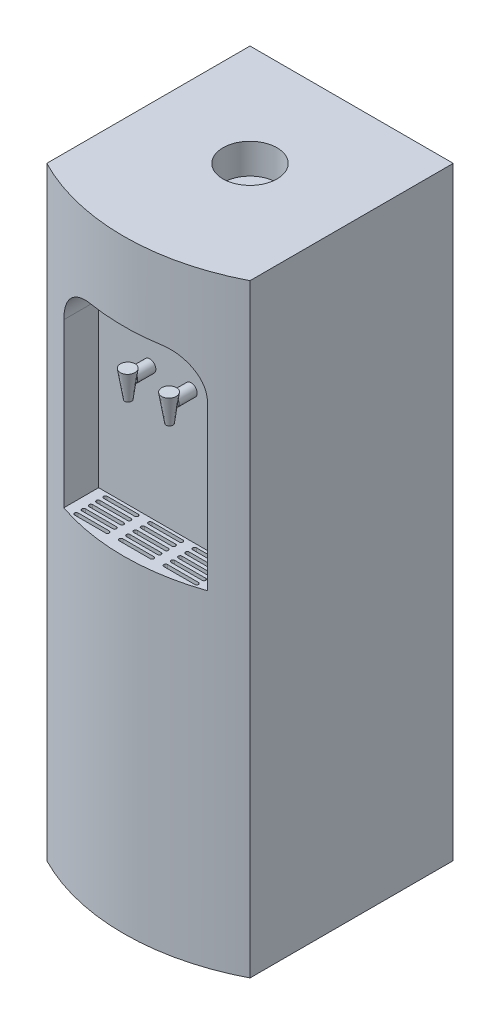
SolidWorks part; units mm, degrees
ref_plane "Front Plane" through (0, 0, 0) normal (0, 0, 1) x (1, 0, 0)
ref_plane "Top Plane" through (0, 0, 0) normal (0, 1, 0) x (1, 0, 0)
ref_plane "Right Plane" through (0, 0, 0) normal (1, 0, 0) x (0, 0, -1)
sketch "Sketch1" plane through (0, 0, 0) normal (0, 1, 0) x (1, 0, 0)
  line L1 (0, 0) -> (42.7396, 0)
  line L2 (0, 0) -> (0, -42.7396)
  line L4 (42.7396, 0) -> (42.7396, -42.7396)
  arc A0 (0, -42.7396) -> (42.7396, -42.7396) centre (21.3698, -1.442) ccw
extrude "Boss-Extrude1" add sketch "Sketch1" along normal blind 127
ref_plane "Plane1" through (0, 0, 127) normal (0, 0, 1) x (1, 0, 0)
sketch "Sketch2" plane through (0, 0, 127) normal (0, 0, 1) x (1, 0, 0)
  line L0 (6.2617, 110.6088) -> (0, 110.6088) construction
  line L1 (13.8817, 110.6088) -> (28.8579, 110.6088)
  line L2 (6.2617, 102.9888) -> (6.2617, 68.7343)
  line L3 (6.2617, 68.7343) -> (36.4779, 68.7343)
  line L4 (36.4779, 102.9888) -> (36.4779, 68.7343)
  line L5 (0, 127) -> (0, 0) construction
  line L6 (36.4779, 110.6088) -> (42.7396, 110.6088) construction
  line L7 (42.7396, 127) -> (42.7396, 0) construction
  arc A0 (28.8579, 110.6088) -> (36.4779, 102.9888) centre (28.8579, 102.9888) cw
  arc A1 (13.8817, 110.6088) -> (6.2617, 102.9888) centre (13.8817, 102.9888) ccw
  dimension "D1" = 7.62
extrude "Cut-Extrude1" cut sketch "Sketch2" against normal blind 88.9
sketch "Sketch4" plane through (0, 68.7343, 0) normal (0, 1, 0) x (1, 0, 0)
  line L0 (6.2617, -38.1) -> (36.4779, -38.1) construction
  line L1 (6.2617, -38.1) -> (36.4779, -38.1) construction
  line L2 (36.4779, -38.1) -> (36.4779, -45.4182) construction
  line L3 (6.2617, -38.1) -> (6.2617, -45.4182) construction
  line L4 (8.7222, -40.6541) -> (15.2596, -40.6541) construction
  line L5 (8.7222, -40.2731) -> (15.2596, -40.2731)
  line L6 (8.7222, -41.0351) -> (15.2596, -41.0351)
  line L7 (18.1011, -40.6541) -> (24.6385, -40.6541) construction
  line L8 (18.1011, -40.2731) -> (24.6385, -40.2731)
  line L9 (18.1011, -41.0351) -> (24.6385, -41.0351)
  line L10 (27.48, -40.6541) -> (34.0174, -40.6541) construction
  line L11 (27.48, -40.2731) -> (34.0174, -40.2731)
  line L12 (27.48, -41.0351) -> (34.0174, -41.0351)
  line L13 (8.3412, -40.6541) -> (6.2617, -40.6541) construction
  line L14 (34.3984, -40.6541) -> (36.4779, -40.6541) construction
  line L15 (15.6406, -40.6541) -> (17.7201, -40.6541) construction
  line L16 (25.0195, -40.6541) -> (27.099, -40.6541) construction
  line L17 (8.7222, -42.1781) -> (15.2596, -42.1781) construction
  line L18 (8.7222, -41.7971) -> (15.2596, -41.7971)
  line L19 (8.7222, -42.5591) -> (15.2596, -42.5591)
  line L20 (18.1011, -42.1781) -> (24.6385, -42.1781) construction
  line L21 (18.1011, -41.7971) -> (24.6385, -41.7971)
  line L22 (18.1011, -42.5591) -> (24.6385, -42.5591)
  line L23 (27.48, -42.1781) -> (34.0174, -42.1781) construction
  line L24 (27.48, -41.7971) -> (34.0174, -41.7971)
  line L25 (27.48, -42.5591) -> (34.0174, -42.5591)
  line L26 (8.7222, -43.7021) -> (15.2596, -43.7021) construction
  line L27 (8.7222, -43.3211) -> (15.2596, -43.3211)
  line L28 (8.7222, -44.0831) -> (15.2596, -44.0831)
  line L29 (18.1011, -43.7021) -> (24.6385, -43.7021) construction
  line L30 (18.1011, -43.3211) -> (24.6385, -43.3211)
  line L31 (18.1011, -44.0831) -> (24.6385, -44.0831)
  line L32 (27.48, -43.7021) -> (34.0174, -43.7021) construction
  line L33 (27.48, -43.3211) -> (34.0174, -43.3211)
  line L34 (27.48, -44.0831) -> (34.0174, -44.0831)
  line L35 (8.7222, -45.2261) -> (15.2596, -45.2261) construction
  line L36 (8.7222, -44.8451) -> (15.2596, -44.8451)
  line L37 (8.7222, -45.6071) -> (15.2596, -45.6071)
  line L38 (18.1011, -45.2261) -> (24.6385, -45.2261) construction
  line L39 (18.1011, -44.8451) -> (24.6385, -44.8451)
  line L40 (18.1011, -45.6071) -> (24.6385, -45.6071)
  line L41 (27.48, -45.2261) -> (34.0174, -45.2261) construction
  line L42 (27.48, -44.8451) -> (34.0174, -44.8451)
  line L43 (27.48, -45.6071) -> (34.0174, -45.6071)
  line L44 (8.7222, -40.6541) -> (15.2596, -40.6541) construction
  line L45 (8.7222, -40.2731) -> (15.2596, -40.2731)
  line L46 (8.7222, -41.0351) -> (15.2596, -41.0351)
  line L47 (18.1011, -40.6541) -> (24.6385, -40.6541) construction
  line L48 (18.1011, -40.2731) -> (24.6385, -40.2731)
  line L49 (18.1011, -41.0351) -> (24.6385, -41.0351)
  line L50 (27.48, -40.6541) -> (34.0174, -40.6541) construction
  line L51 (27.48, -40.2731) -> (34.0174, -40.2731)
  line L52 (27.48, -41.0351) -> (34.0174, -41.0351)
  line L53 (8.7222, -42.1781) -> (15.2596, -42.1781) construction
  line L54 (8.7222, -41.7971) -> (15.2596, -41.7971)
  line L55 (8.7222, -42.5591) -> (15.2596, -42.5591)
  line L56 (18.1011, -42.1781) -> (24.6385, -42.1781) construction
  line L57 (18.1011, -41.7971) -> (24.6385, -41.7971)
  line L58 (18.1011, -42.5591) -> (24.6385, -42.5591)
  line L59 (27.48, -42.1781) -> (34.0174, -42.1781) construction
  line L60 (27.48, -41.7971) -> (34.0174, -41.7971)
  line L61 (27.48, -42.5591) -> (34.0174, -42.5591)
  line L62 (8.7222, -43.7021) -> (15.2596, -43.7021) construction
  line L63 (8.7222, -43.3211) -> (15.2596, -43.3211)
  line L64 (8.7222, -44.0831) -> (15.2596, -44.0831)
  line L65 (18.1011, -43.7021) -> (24.6385, -43.7021) construction
  line L66 (18.1011, -43.3211) -> (24.6385, -43.3211)
  line L67 (18.1011, -44.0831) -> (24.6385, -44.0831)
  line L68 (27.48, -43.7021) -> (34.0174, -43.7021) construction
  line L69 (27.48, -43.3211) -> (34.0174, -43.3211)
  line L70 (27.48, -44.0831) -> (34.0174, -44.0831)
  line L71 (8.7222, -39.1301) -> (15.2596, -39.1301) construction
  line L72 (8.7222, -38.7491) -> (15.2596, -38.7491)
  line L73 (8.7222, -39.5111) -> (15.2596, -39.5111)
  line L74 (18.1011, -39.1301) -> (24.6385, -39.1301) construction
  line L75 (18.1011, -38.7491) -> (24.6385, -38.7491)
  line L76 (18.1011, -39.5111) -> (24.6385, -39.5111)
  line L77 (27.48, -39.1301) -> (34.0174, -39.1301) construction
  line L78 (27.48, -38.7491) -> (34.0174, -38.7491)
  line L79 (27.48, -39.5111) -> (34.0174, -39.5111)
  arc A0 (8.7222, -40.2731) -> (8.7222, -41.0351) centre (8.7222, -40.6541) ccw
  arc A1 (15.2596, -41.0351) -> (15.2596, -40.2731) centre (15.2596, -40.6541) ccw
  arc A2 (18.1011, -40.2731) -> (18.1011, -41.0351) centre (18.1011, -40.6541) ccw
  arc A3 (24.6385, -41.0351) -> (24.6385, -40.2731) centre (24.6385, -40.6541) ccw
  arc A4 (27.48, -40.2731) -> (27.48, -41.0351) centre (27.48, -40.6541) ccw
  arc A5 (34.0174, -41.0351) -> (34.0174, -40.2731) centre (34.0174, -40.6541) ccw
  arc A6 (8.7222, -41.7971) -> (8.7222, -42.5591) centre (8.7222, -42.1781) ccw
  arc A7 (15.2596, -42.5591) -> (15.2596, -41.7971) centre (15.2596, -42.1781) ccw
  arc A8 (18.1011, -41.7971) -> (18.1011, -42.5591) centre (18.1011, -42.1781) ccw
  arc A9 (24.6385, -42.5591) -> (24.6385, -41.7971) centre (24.6385, -42.1781) ccw
  arc A10 (27.48, -41.7971) -> (27.48, -42.5591) centre (27.48, -42.1781) ccw
  arc A11 (34.0174, -42.5591) -> (34.0174, -41.7971) centre (34.0174, -42.1781) ccw
  arc A12 (8.7222, -43.3211) -> (8.7222, -44.0831) centre (8.7222, -43.7021) ccw
  arc A13 (15.2596, -44.0831) -> (15.2596, -43.3211) centre (15.2596, -43.7021) ccw
  arc A14 (18.1011, -43.3211) -> (18.1011, -44.0831) centre (18.1011, -43.7021) ccw
  arc A15 (24.6385, -44.0831) -> (24.6385, -43.3211) centre (24.6385, -43.7021) ccw
  arc A16 (27.48, -43.3211) -> (27.48, -44.0831) centre (27.48, -43.7021) ccw
  arc A17 (34.0174, -44.0831) -> (34.0174, -43.3211) centre (34.0174, -43.7021) ccw
  arc A18 (8.7222, -44.8451) -> (8.7222, -45.6071) centre (8.7222, -45.2261) ccw
  arc A19 (15.2596, -45.6071) -> (15.2596, -44.8451) centre (15.2596, -45.2261) ccw
  arc A20 (18.1011, -44.8451) -> (18.1011, -45.6071) centre (18.1011, -45.2261) ccw
  arc A21 (24.6385, -45.6071) -> (24.6385, -44.8451) centre (24.6385, -45.2261) ccw
  arc A22 (27.48, -44.8451) -> (27.48, -45.6071) centre (27.48, -45.2261) ccw
  arc A23 (34.0174, -45.6071) -> (34.0174, -44.8451) centre (34.0174, -45.2261) ccw
  arc A24 (8.7222, -40.2731) -> (8.7222, -41.0351) centre (8.7222, -40.6541) ccw
  arc A25 (15.2596, -41.0351) -> (15.2596, -40.2731) centre (15.2596, -40.6541) ccw
  arc A26 (18.1011, -40.2731) -> (18.1011, -41.0351) centre (18.1011, -40.6541) ccw
  arc A27 (24.6385, -41.0351) -> (24.6385, -40.2731) centre (24.6385, -40.6541) ccw
  arc A28 (27.48, -40.2731) -> (27.48, -41.0351) centre (27.48, -40.6541) ccw
  arc A29 (34.0174, -41.0351) -> (34.0174, -40.2731) centre (34.0174, -40.6541) ccw
  arc A30 (8.7222, -41.7971) -> (8.7222, -42.5591) centre (8.7222, -42.1781) ccw
  arc A31 (15.2596, -42.5591) -> (15.2596, -41.7971) centre (15.2596, -42.1781) ccw
  arc A32 (18.1011, -41.7971) -> (18.1011, -42.5591) centre (18.1011, -42.1781) ccw
  arc A33 (24.6385, -42.5591) -> (24.6385, -41.7971) centre (24.6385, -42.1781) ccw
  arc A34 (27.48, -41.7971) -> (27.48, -42.5591) centre (27.48, -42.1781) ccw
  arc A35 (34.0174, -42.5591) -> (34.0174, -41.7971) centre (34.0174, -42.1781) ccw
  arc A36 (8.7222, -43.3211) -> (8.7222, -44.0831) centre (8.7222, -43.7021) ccw
  arc A37 (15.2596, -44.0831) -> (15.2596, -43.3211) centre (15.2596, -43.7021) ccw
  arc A38 (18.1011, -43.3211) -> (18.1011, -44.0831) centre (18.1011, -43.7021) ccw
  arc A39 (24.6385, -44.0831) -> (24.6385, -43.3211) centre (24.6385, -43.7021) ccw
  arc A40 (27.48, -43.3211) -> (27.48, -44.0831) centre (27.48, -43.7021) ccw
  arc A41 (34.0174, -44.0831) -> (34.0174, -43.3211) centre (34.0174, -43.7021) ccw
  arc A42 (8.7222, -38.7491) -> (8.7222, -39.5111) centre (8.7222, -39.1301) ccw
  arc A43 (15.2596, -39.5111) -> (15.2596, -38.7491) centre (15.2596, -39.1301) ccw
  arc A44 (18.1011, -38.7491) -> (18.1011, -39.5111) centre (18.1011, -39.1301) ccw
  arc A45 (24.6385, -39.5111) -> (24.6385, -38.7491) centre (24.6385, -39.1301) ccw
  arc A46 (27.48, -38.7491) -> (27.48, -39.5111) centre (27.48, -39.1301) ccw
  arc A47 (34.0174, -39.5111) -> (34.0174, -38.7491) centre (34.0174, -39.1301) ccw
  point P12 (11.9909, -40.6541)
  point P17 (21.3698, -40.6541)
  point P26 (30.7487, -40.6541)
  point P43 (11.9909, -42.1781)
  point P48 (21.3698, -42.1781)
  point P57 (30.7487, -42.1781)
  point P64 (11.9909, -43.7021)
  point P69 (21.3698, -43.7021)
  point P78 (30.7487, -43.7021)
  point P85 (11.9909, -45.2261)
  point P90 (21.3698, -45.2261)
  point P99 (30.7487, -45.2261)
  point P106 (11.9909, -40.6541)
  point P111 (21.3698, -40.6541)
  point P120 (30.7487, -40.6541)
  point P127 (11.9909, -42.1781)
  point P132 (21.3698, -42.1781)
  point P141 (30.7487, -42.1781)
  point P148 (11.9909, -43.7021)
  point P153 (21.3698, -43.7021)
  point P162 (30.7487, -43.7021)
  point P169 (11.9909, -39.1301)
  point P174 (21.3698, -39.1301)
  point P183 (30.7487, -39.1301)
  dimension "D1" = 0.762
  dimension "D2" = 4
  dimension "D3" = 2
extrude "Cut-Extrude2" cut sketch "Sketch4" against normal blind 1.27 contours L40 A21 L39 A20 | L37 A19 L36 A18 | L19 A7 L18 A6 | L28 A13 L27 A12 | L31 A15 L30 A14 | L22 A9 L21 A8 | L9 A3 L8 A2 | L76 A45 L75 A44 | L6 A1 L5 A0 | L73 A43 L72 A42 | L34 A17 L33 A16 | L25 A11 L24 A10 | L12 A5 L11 A4 | L79 A47 L78 A46 | A22 L43 A23 L42
sketch "Sketch5" plane through (0, 127, 0) normal (0, 1, 0) x (1, 0, 0)
  line L0 (0, -21.3698) -> (42.7396, -21.3698)
  line L2 (0, 0) -> (0, -42.7396) construction
  line L4 (42.7396, -42.7396) -> (42.7396, 0) construction
  circle A0 centre (21.3698, -21.3698) radius 5.689
extrude "Cut-Extrude3" cut sketch "Sketch5" against normal blind 6.35 contours L0 A0 | L0 A0
sketch "Sketch6" plane through (0, 0, 38.1) normal (0, 0, 1) x (1, 0, 0)
  line L0 (8.3412, 67.4643) -> (8.3412, 105.8503) construction
  line L1 (34.3984, 67.4643) -> (34.3984, 105.8503) construction
  line L2 (17.0269, 96.3161) -> (8.3412, 96.3161) construction
  line L3 (17.0269, 96.3161) -> (25.7127, 96.3161) construction
  line L4 (25.7127, 96.3161) -> (34.3984, 96.3161) construction
  circle A2 centre (17.0269, 96.3161) radius 1.27
  circle A3 centre (25.7127, 96.3161) radius 1.27
  dimension "D1" = 2.54
extrude "Boss-Extrude2" add sketch "Sketch6" along normal blind 3.81
sketch "Sketch7" plane through (0, 0, 41.91) normal (0, 0, 1) x (1, 0, 0)
  line L0 (17.0269, 95.0461) -> (17.0269, 97.5861) construction
ref_plane "Plane2" through (17.0269, 0, 0) normal (1, 0, 0) x (0, 1, 0)
sketch "Sketch8" plane through (17.0269, 0, 0) normal (1, 0, 0) x (0, 1, 0)
  line L0 (92.4628, 42.6259) -> (92.4628, 43.3418)
  line L2 (92.4628, 43.3418) -> (98.1731, 44.2935)
  line L3 (98.1731, 44.2935) -> (98.1731, 42.7396)
  line L5 (92.4628, 42.6259) -> (98.1731, 42.7396) construction
  line L6 (127, 42.7396) -> (0, 42.7396) construction
  line L7 (92.4628, 42.6259) -> (98.1731, 42.7396)
revolve "Revolve1" add sketch "Sketch8" angle 360 about L5
sketch "Sketch9" plane through (0, 0, 38.1) normal (0, 0, 1) x (1, 0, 0)
  line L0 (21.3698, 110.6088) -> (21.3698, 56.3623) construction
ref_plane "Plane3" through (21.3698, 0, 0) normal (-1, 0, 0) x (0, -1, 0)
mirror "Mirror1" about plane through (21.3698, 0, 0) normal (-1, 0, 0) of "Revolve1"
